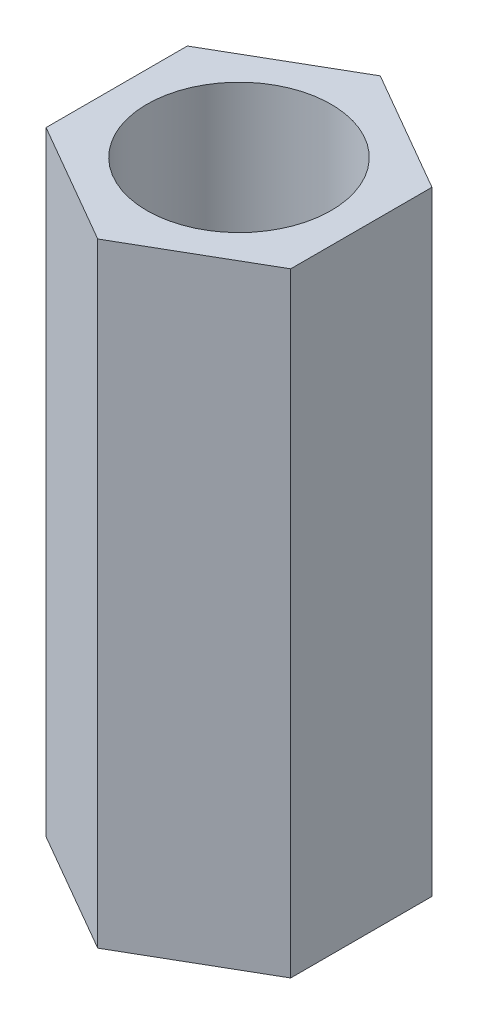
SolidWorks part; units mm, degrees
material "黄铜"
ref_plane "前视基准面" through (0, 0, 0) normal (0, 0, 1) x (1, 0, 0)
ref_plane "上视基准面" through (0, 0, 0) normal (0, 1, 0) x (1, 0, 0)
ref_plane "右视基准面" through (0, 0, 0) normal (1, 0, 0) x (0, 0, -1)
other "Configuration Table"
sketch "草图1" plane through (0, 0, 0) normal (0, 1, 0) x (1, 0, 0)
  line L0 (0, 0) -> (0, 3.0947) construction
  line L1 (1.9919, 1.15) -> (0, 2.3)
  line L2 (0, 2.3) -> (-1.9919, 1.15)
  line L3 (-1.9919, 1.15) -> (-1.9919, -1.15)
  line L4 (-1.9919, -1.15) -> (0, -2.3)
  line L5 (0, -2.3) -> (1.9919, -1.15)
  line L6 (1.9919, -1.15) -> (1.9919, 1.15)
  circle A0 centre (0, 0) radius 1.5
  circle A1 centre (0, 0) radius 1.9919 construction
  dimension "D1" = 3
  dimension "D2" = 4.6
extrude "凸台-拉伸1" add sketch "草图1" along normal blind 10
